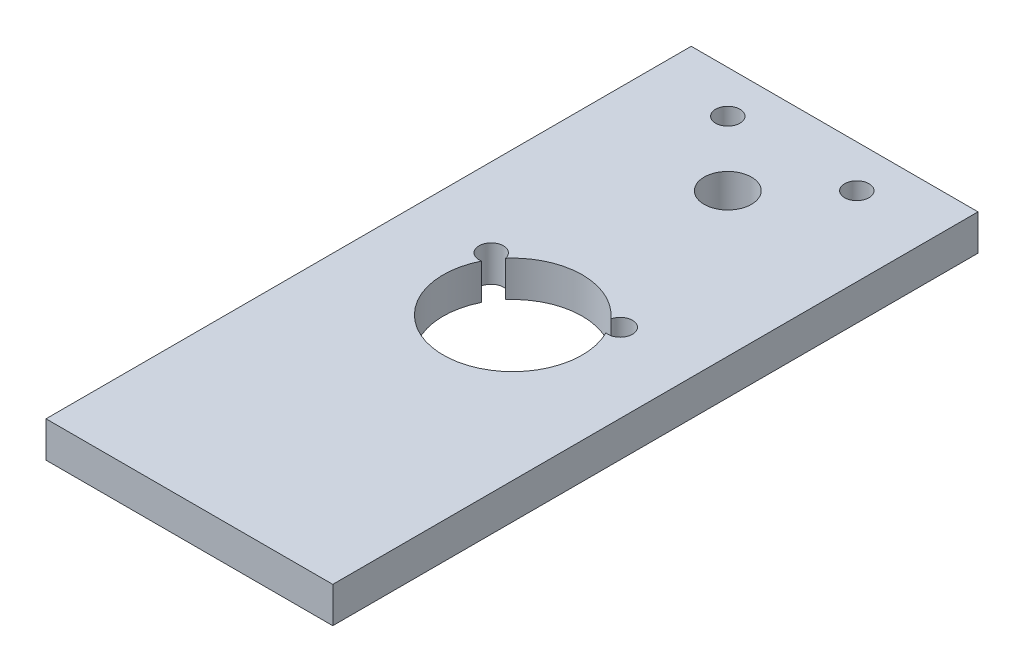
SolidWorks part; units mm, degrees
ref_plane "Front Plane" through (0, 0, 0) normal (0, 0, 1) x (1, 0, 0)
ref_plane "Top Plane" through (0, 0, 0) normal (0, 1, 0) x (1, 0, 0)
ref_plane "Right Plane" through (0, 0, 0) normal (1, 0, 0) x (0, 0, -1)
sketch "Sketch2" plane through (0, 0, 0) normal (0, 1, 0) x (1, 0, 0)
  line L1 (0, 0) -> (40, 0)
  line L2 (0, 0) -> (0, 90)
  line L3 (0, 90) -> (40, 90)
  line L4 (40, 0) -> (40, 90)
  dimension "D1" = 90
  dimension "D2" = 40
extrude "Boss-Extrude1" add sketch "Sketch2" along normal blind 5
sketch "Sketch3" plane through (0, 5, 0) normal (0, 1, 0) x (1, 0, 0)
  line L0 (20, 90) -> (20, 0) construction
  line L1 (40, 90) -> (0, 90) construction
  line L2 (0, 0) -> (40, 0) construction
  line L3 (0, 45) -> (40, 45) construction
  line L4 (0, 90) -> (0, 0) construction
  line L5 (40, 0) -> (40, 90) construction
  circle A0 centre (20, 75.1) radius 3.3
  circle A1 centre (20, 45.1) radius 9.7
  dimension "D1" = 6.6
  dimension "D4" = 19.4
  dimension "D2" = 14.9
  dimension "D3" = 30
extrude "Cut-Extrude1" cut sketch "Sketch3" against normal through all contours A0 | A1
sketch "Sketch5" plane through (0, 5, 0) normal (0, 1, 0) x (1, 0, 0)
  circle A0 centre (11, 84.1) radius 1.7
  circle A1 centre (20, 75.1) radius 3.3 construction
  circle A2 centre (11, 51.1) radius 1.7
  dimension "D1" = 3.4
  dimension "D2" = 9
  dimension "D3" = 9
  dimension "D4" = 24
extrude "Cut-Extrude2" cut sketch "Sketch5" against normal through all
ref_plane "Plane1" through (20, 0, 0) normal (1, 0, 0) x (0, 0, -1)
mirror "Mirror1" about plane through (20, 0, 0) normal (1, 0, 0) of "Cut-Extrude2"
